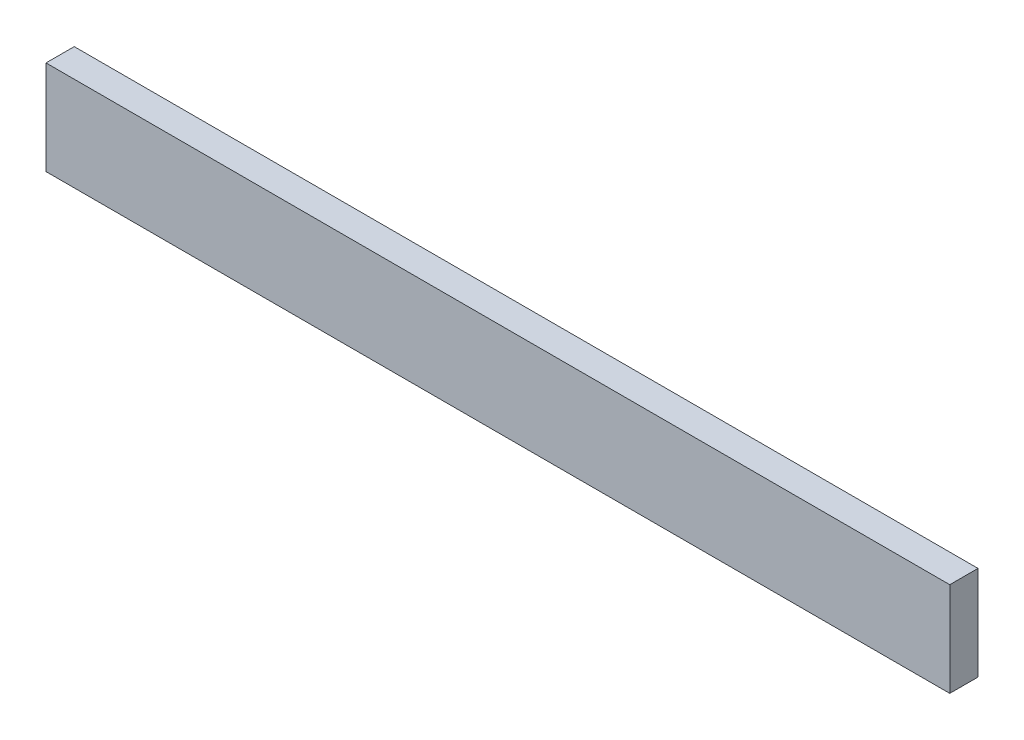
SolidWorks part; units mm, degrees
ref_plane "Front Plane" through (0, 0, 0) normal (0, 0, 1) x (1, 0, 0)
ref_plane "Top Plane" through (0, 0, 0) normal (0, 1, 0) x (1, 0, 0)
ref_plane "Right Plane" through (0, 0, 0) normal (1, 0, 0) x (0, 0, -1)
sketch "Sketch1" plane through (0, 0, 0) normal (0, 0, 1) x (1, 0, 0)
  line L0 (-63.1494, 3.3207) -> (32.8506, 3.3207)
  line L1 (32.8506, 3.3207) -> (32.8506, -6.6793)
  line L2 (32.8506, -6.6793) -> (-63.1494, -6.6793)
  line L3 (-63.1494, -6.6793) -> (-63.1494, 3.3207)
extrude "Boss-Extrude1" add sketch "Sketch1" along normal blind 3
